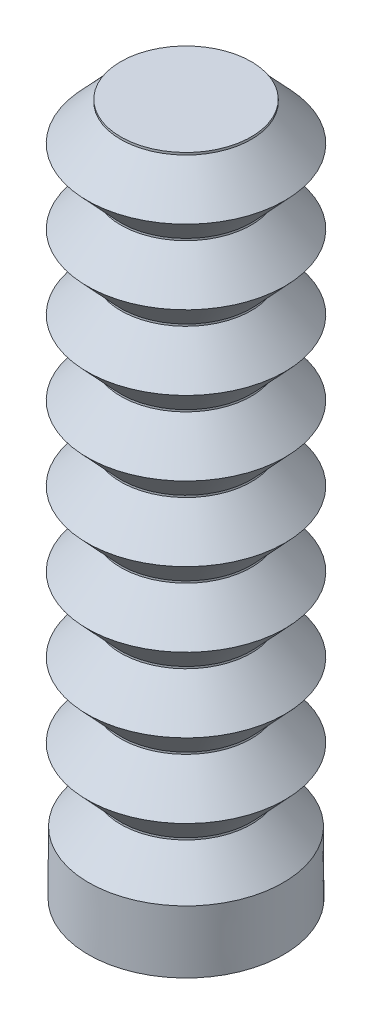
SolidWorks part; units mm, degrees
ref_plane "Front Plane" through (0, 0, 0) normal (0, 0, 1) x (1, 0, 0)
ref_plane "Top Plane" through (0, 0, 0) normal (0, 1, 0) x (1, 0, 0)
ref_plane "Right Plane" through (0, 0, 0) normal (1, 0, 0) x (0, 0, -1)
sketch "Sketch1" plane through (0, 0, 0) normal (0, 0, 1) x (1, 0, 0)
  line L1 (-2.1316, 34.103) -> (-2.1316, 33.9884)
  line L2 (-5.4316, 34.103) -> (-5.4316, -0.9) construction
  line L3 (-2.1316, 33.9884) -> (-2.1316, 30.3384) construction
  line L4 (-2.1316, 32.1634) -> (-0.4316, 32.1634) construction
  line L5 (-2.1316, 33.9884) -> (-0.4316, 32.1634)
  line L6 (-2.1316, 34.103) -> (-5.4316, 34.103)
  line L7 (-0.4316, 32.1634) -> (-2.1316, 30.3384)
  line L8 (-2.1316, 30.3384) -> (-2.1316, 30.2384)
  line L9 (-2.1316, 26.5884) -> (-2.1316, 26.4884)
  line L10 (-0.4316, 28.4134) -> (-2.1316, 26.5884)
  line L11 (-2.1316, 30.2384) -> (-0.4316, 28.4134)
  line L12 (-2.1316, 22.8384) -> (-2.1316, 22.7384)
  line L13 (-0.4316, 24.6634) -> (-2.1316, 22.8384)
  line L14 (-2.1316, 26.4884) -> (-0.4316, 24.6634)
  line L15 (-2.1316, 19.0884) -> (-2.1316, 18.9884)
  line L16 (-0.4316, 20.9134) -> (-2.1316, 19.0884)
  line L17 (-2.1316, 22.7384) -> (-0.4316, 20.9134)
  line L18 (-2.1316, 15.3384) -> (-2.1316, 15.2384)
  line L19 (-0.4316, 17.1634) -> (-2.1316, 15.3384)
  line L20 (-2.1316, 18.9884) -> (-0.4316, 17.1634)
  line L21 (-2.1316, 11.5884) -> (-2.1316, 11.4884)
  line L22 (-0.4316, 13.4134) -> (-2.1316, 11.5884)
  line L23 (-2.1316, 15.2384) -> (-0.4316, 13.4134)
  line L24 (-2.1316, 7.8384) -> (-2.1316, 7.7384)
  line L25 (-0.4316, 9.6634) -> (-2.1316, 7.8384)
  line L26 (-2.1316, 11.4884) -> (-0.4316, 9.6634)
  line L27 (-2.1316, 4.0884) -> (-2.1316, 3.9884)
  line L28 (-0.4316, 5.9134) -> (-2.1316, 4.0884)
  line L29 (-2.1316, 7.7384) -> (-0.4316, 5.9134)
  line L30 (-2.1316, 3.9884) -> (-0.5131, 2.2455)
  line L31 (-0.5131, 2.2455) -> (-0.4951, -0.9)
  line L32 (-5.4316, 34.103) -> (-5.4316, -0.9)
  line L33 (-5.4316, -0.9) -> (-0.4951, -0.9)
  dimension "D1" = 8
  dimension "D3" = 3.3
revolve "Revolve3" add sketch "Sketch1" angle 360 about L32
